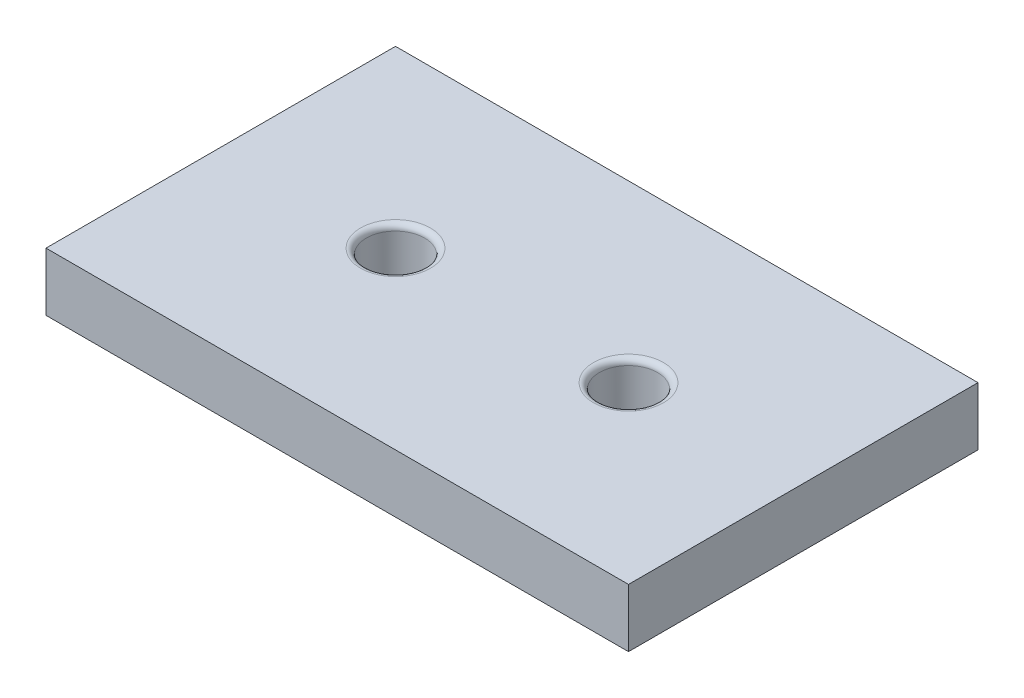
SolidWorks part; units mm, degrees
ref_plane "前视基准面" through (0, 0, 0) normal (0, 0, 1) x (1, 0, 0)
ref_plane "上视基准面" through (0, 0, 0) normal (0, 1, 0) x (1, 0, 0)
ref_plane "右视基准面" through (0, 0, 0) normal (1, 0, 0) x (0, 0, -1)
other "Configuration Table"
sketch "草图1" plane through (0, 0, 0) normal (0, 1, 0) x (1, 0, 0)
  line L1 (-50, -30) -> (50, -30)
  line L2 (-50, -30) -> (-50, 30)
  line L3 (-50, 30) -> (50, 30)
  line L4 (50, -30) -> (50, 30)
  line L5 (-50, -30) -> (50, 30) construction
  line L6 (-50, 30) -> (50, -30) construction
extrude "凸台-拉伸1" add sketch "草图1" along normal blind 10
sketch "草图2" plane through (0, 0, 0) normal (0, 1, 0) x (1, 0, 0)
  circle A0 centre (-20, 0) radius 5
extrude "切除-拉伸1" cut sketch "草图2" along normal blind 20
sketch "草图3" plane through (0, 0, 0) normal (0, 1, 0) x (1, 0, 0)
  circle A0 centre (20, 0) radius 5
extrude "切除-拉伸2" cut sketch "草图3" along normal blind 20
fillet "圆角1" radius 1 2 edges at (20, 10, -5) (-20, 10, -5)
sketch "草图4" plane through (0, 0, 0) normal (0, 1, 0) x (1, 0, 0)
  line L0 (-10, -20) -> (10, -20)
